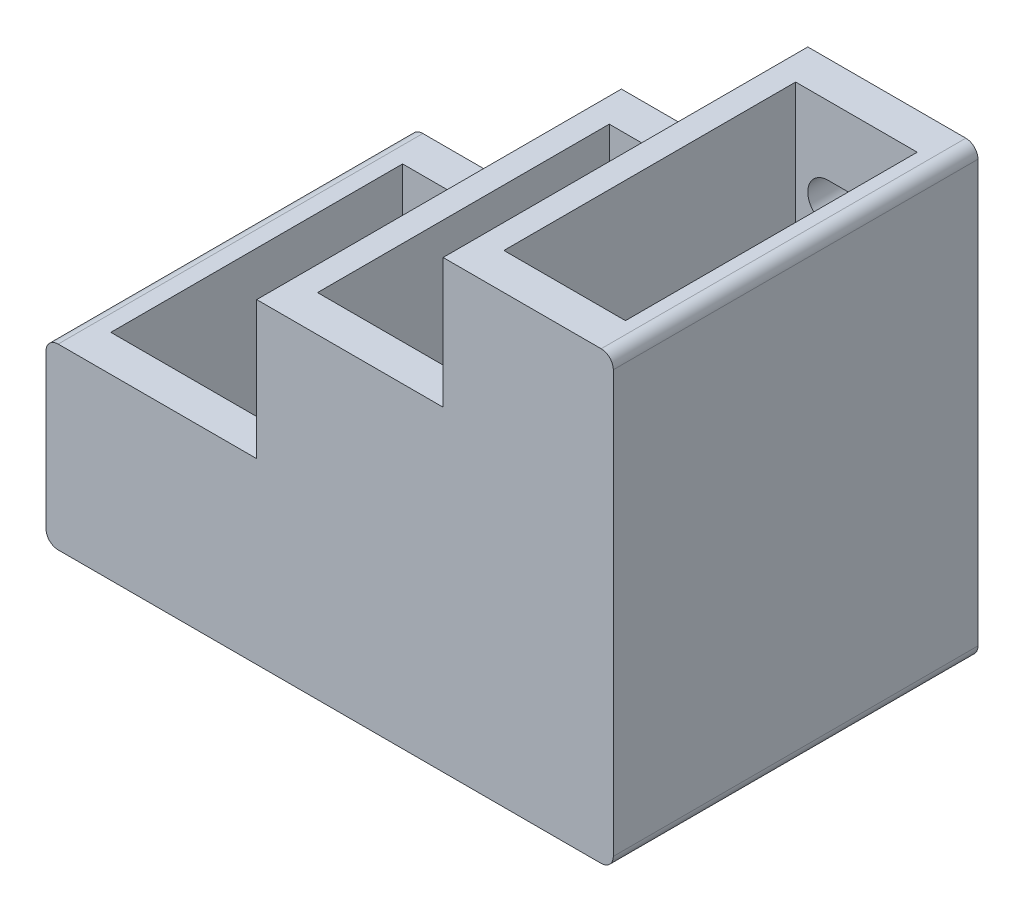
SolidWorks part; units mm, degrees
ref_plane "前视基准面" through (0, 0, 0) normal (0, 0, 1) x (1, 0, 0)
ref_plane "上视基准面" through (0, 0, 0) normal (0, 1, 0) x (1, 0, 0)
ref_plane "右视基准面" through (0, 0, 0) normal (1, 0, 0) x (0, 0, -1)
sketch "草图1" plane through (0, 0, 0) normal (0, 0, 1) x (1, 0, 0)
  line L0 (-70, 0) -> (70, 0)
  line L1 (70, 0) -> (70, 110)
  line L2 (70, 110) -> (28, 110)
  line L3 (28, 110) -> (28, 78)
  line L4 (28, 78) -> (-18, 78)
  line L5 (-18, 78) -> (-18, 44)
  line L6 (-18, 44) -> (-70, 44)
  line L7 (-70, 44) -> (-70, 0)
extrude "凸台-拉伸1" add sketch "草图1" along normal blind 90
ref_plane "基准面1" through (0, 44, 0) normal (0, 1, 0) x (1, 0, 0)
sketch "草图2" plane through (0, 44, 0) normal (0, 1, 0) x (1, 0, 0)
  line L0 (-63, -9) -> (-25, -9)
  line L1 (-25, -9) -> (-25, -81)
  line L2 (-25, -81) -> (-63, -81)
  line L3 (-63, -81) -> (-63, -9)
extrude "切除-拉伸1" cut sketch "草图2" against normal blind 36
ref_plane "基准面2" through (0, 78, 0) normal (0, 1, 0) x (1, 0, 0)
sketch "草图4" plane through (0, 78, 0) normal (0, 1, 0) x (1, 0, 0)
  line L0 (-12, -9) -> (22, -9)
  line L1 (22, -9) -> (22, -81)
  line L2 (22, -81) -> (-12, -81)
  line L3 (-12, -81) -> (-12, -9)
extrude "切除-拉伸3" cut sketch "草图4" against normal blind 70
ref_plane "基准面3" through (0, 110, 0) normal (0, 1, 0) x (1, 0, 0)
sketch "草图5" plane through (0, 110, 0) normal (0, 1, 0) x (1, 0, 0)
  line L0 (34, -9) -> (64, -9)
  line L1 (64, -9) -> (64, -81)
  line L2 (64, -81) -> (34, -81)
  line L3 (34, -81) -> (34, -9)
extrude "切除-拉伸4" cut sketch "草图5" against normal blind 102
sketch "草图7" plane through (0, 0, 0) normal (0, 1, 0) x (1, 0, 0)
  line L0 (-57, -38) -> (-31, -38)
  line L1 (-31, -38) -> (-31, -52)
  line L2 (-31, -52) -> (-57, -52)
  line L3 (-57, -52) -> (-57, -38)
  line L4 (36, -38) -> (62, -38)
  line L5 (62, -38) -> (62, -52)
  line L6 (62, -52) -> (36, -52)
  line L7 (36, -52) -> (36, -38)
extrude "切除-拉伸6" cut sketch "草图7" along normal blind 1.5
fillet "圆角2" radius 3 4 edges at (70, 110, 45) (70, 0, 45) (-70, 44, 45) (-70, 0, 45)
sketch "草图12" plane through (0, 0, 0) normal (0, 0, 1) x (1, 0, 0)
  line L0 (-49.5, 27) -> (-38.5, 27)
  line L1 (-37, 28.5) -> (-37, 35.5)
  line L2 (-38.5, 37) -> (-49.5, 37)
  line L3 (-51, 35.5) -> (-51, 28.5)
  arc A0 (-51, 28.5) -> (-49.5, 27) centre (-49.5, 28.5) ccw
  arc A1 (-38.5, 27) -> (-37, 28.5) centre (-38.5, 28.5) ccw
  arc A2 (-37, 35.5) -> (-38.5, 37) centre (-38.5, 35.5) ccw
  arc A3 (-49.5, 37) -> (-51, 35.5) centre (-49.5, 35.5) ccw
extrude "切除-拉伸11" cut sketch "草图12" along normal blind 9.5
sketch "草图13" plane through (0, 0, 0) normal (0, 0, 1) x (1, 0, 0)
  line L0 (42, 83) -> (56, 83)
  line L1 (56, 93) -> (42, 93)
  arc A0 (56, 83) -> (56, 93) centre (56, 88) ccw
  arc A1 (42, 93) -> (42, 83) centre (42, 88) ccw
extrude "切除-拉伸12" cut sketch "草图13" along normal blind 9.5
